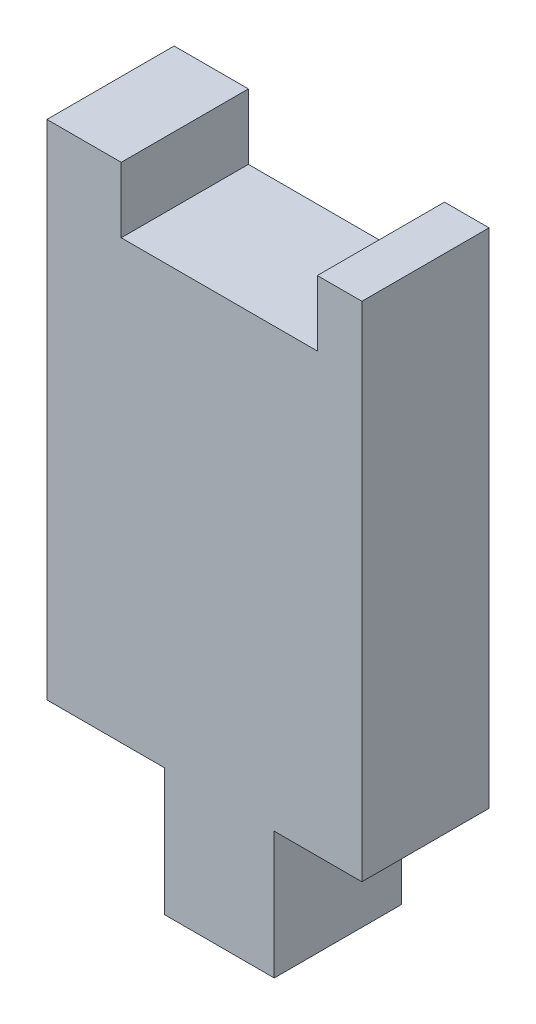
SolidWorks part; units mm, degrees
ref_plane "Front Plane" through (0, 0, 0) normal (0, 0, 1) x (1, 0, 0)
ref_plane "Top Plane" through (0, 0, 0) normal (0, 1, 0) x (1, 0, 0)
ref_plane "Right Plane" through (0, 0, 0) normal (1, 0, 0) x (0, 0, -1)
sketch "Sketch1" plane through (0, 0, 0) normal (0, 0, 1) x (1, 0, 0)
  line L1 (0, 0) -> (12.192, 0)
  line L2 (0, 0) -> (0, 24.384)
  line L3 (0, 24.384) -> (12.192, 24.384)
  line L4 (12.192, 0) -> (12.192, 24.384)
  dimension "D1" = 12.192
  dimension "D2" = 24.384
extrude "Boss-Extrude1" add sketch "Sketch1" along normal blind 5.4356
sketch "Sketch2" plane through (0, 0, 5.4356) normal (0, 0, 1) x (1, 0, 0)
  line L0 (6.096, -1000) -> (6.096, 49000) construction
  line L1 (0, 0) -> (12.192, 0) construction
  line L2 (3.7465, 3.8359) -> (6.096, 3.8359) construction
  line L3 (6.096, 2.3287) -> (8.4455, 2.3287) construction
  line L4 (3.7465, 0) -> (3.7465, 5.4356)
  line L6 (8.4455, 0) -> (8.4455, 5.4356)
  line L8 (3.7465, 5.4356) -> (0, 5.4356)
  line L9 (0, 24.384) -> (0, 0) construction
  line L10 (0, 5.4356) -> (0, 0)
  line L11 (0, 0) -> (3.7465, 0)
  line L12 (8.4455, 5.4356) -> (12.192, 5.4356)
  line L13 (12.192, 0) -> (12.192, 24.384) construction
  line L14 (12.192, 5.4356) -> (12.192, 0)
  line L15 (12.192, 0) -> (8.4455, 0)
  point P5 (6.096, 0)
  dimension "D1" = 5.4356
  dimension "D2" = 4.699
  dimension "D4" = 5.4356
extrude "Cut-Extrude1" cut sketch "Sketch2" against normal blind 5.4356
sketch "Sketch3" plane through (0, 0, 5.4356) normal (0, 0, 1) x (1, 0, 0)
  line L2 (0, 24.384) -> (0, 27.178)
  line L3 (0, 27.178) -> (1.905, 27.178)
  line L4 (1.905, 27.178) -> (1.905, 24.384)
  line L7 (12.192, 24.384) -> (0, 24.384) construction
  line L10 (12.192, 24.384) -> (12.192, 27.178)
  line L11 (12.192, 27.178) -> (10.287, 27.178)
  line L12 (10.287, 27.178) -> (10.287, 24.384)
  line L15 (0, 24.384) -> (1.905, 24.384)
  line L16 (10.287, 24.384) -> (12.192, 24.384)
  dimension "D2" = 2.794
  dimension "D4" = 1.905
extrude "Boss-Extrude2" add sketch "Sketch3" against normal up to surface (5.4356 mm away) up to face at (6.096, 8.8138, 0)
sketch "Sketch4" plane through (0, 0, 5.4356) normal (0, 0, 1) x (1, 0, 0)
  line L0 (3.7465, 5.4356) -> (0, 5.4356) construction
  line L1 (0, 27.178) -> (-1.27, 27.178)
  line L2 (0, 27.178) -> (0, 5.4356)
  line L3 (0, 5.4356) -> (-1.27, 5.4356)
  line L4 (-1.27, 27.178) -> (-1.27, 5.4356)
  dimension "D1" = 1.27
extrude "Boss-Extrude3" add sketch "Sketch4" against normal up to surface (5.4356 mm away) up to face at (6.4452, 14.8188, 0)
sketch "Sketch5" plane through (0, 0, 5.4356) normal (0, 0, 1) x (1, 0, 0)
  line L0 (1.905, 24.384) -> (1.905, 27.178) construction
  line L1 (-1.27, 27.178) -> (1.905, 27.178)
  line L2 (-1.27, 27.178) -> (-1.27, 26.924)
  line L3 (-1.27, 26.924) -> (1.905, 26.924)
  line L4 (1.905, 27.178) -> (1.905, 26.924)
  line L5 (12.192, 5.4356) -> (12.192, 27.178) construction
  line L6 (10.287, 27.178) -> (12.192, 27.178)
  line L7 (10.287, 27.178) -> (10.287, 26.924)
  line L8 (10.287, 26.924) -> (12.192, 26.924)
  line L9 (12.192, 27.178) -> (12.192, 26.924)
  line L10 (10.287, 27.178) -> (10.287, 24.384) construction
  line L11 (1.905, 24.384) -> (10.287, 24.384)
  line L12 (1.905, 24.384) -> (1.905, 24.13)
  line L13 (1.905, 24.13) -> (10.287, 24.13)
  line L14 (10.287, 24.384) -> (10.287, 24.13)
  dimension "D1" = 0.254
  dimension "D2" = 0.254
extrude "Cut-Extrude2" cut sketch "Sketch5" against normal through all
